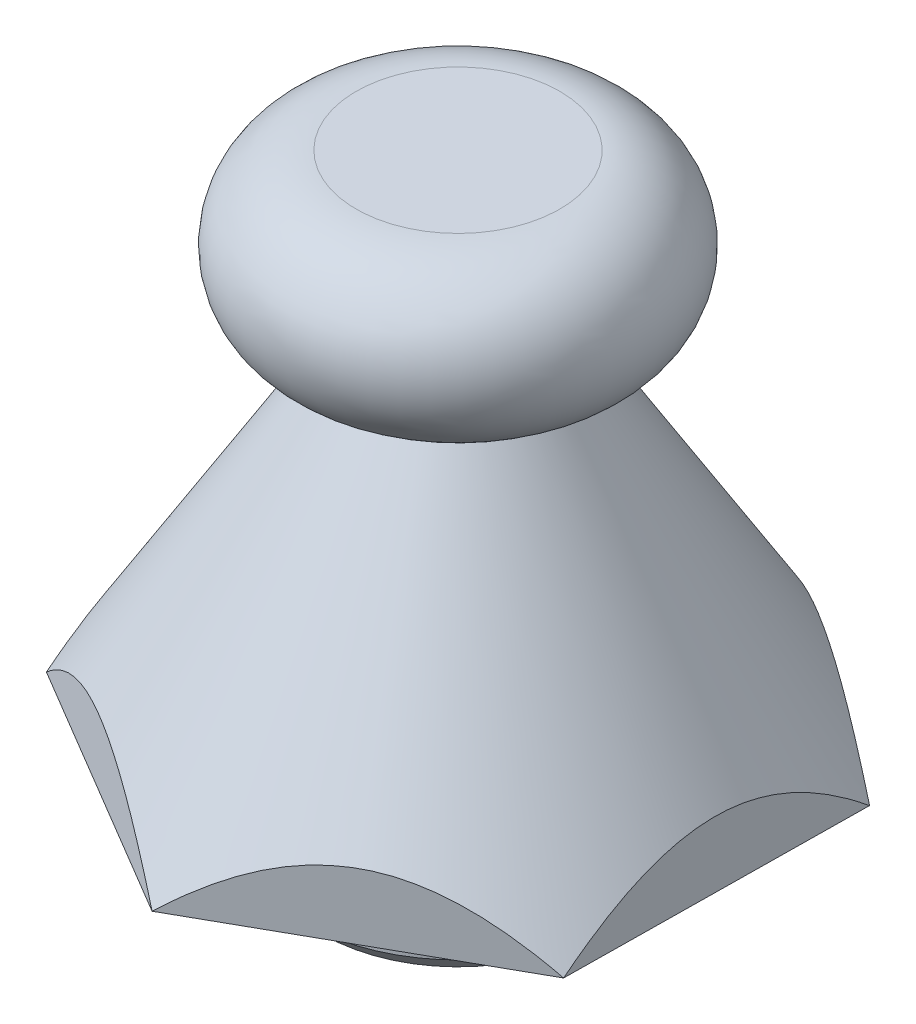
SolidWorks part; units mm, degrees
ref_plane "Front Plane" through (0, 0, 0) normal (0, 0, 1) x (1, 0, 0)
ref_plane "Top Plane" through (0, 0, 0) normal (0, 1, 0) x (1, 0, 0)
ref_plane "Right Plane" through (0, 0, 0) normal (1, 0, 0) x (0, 0, -1)
sketch "Sketch1" plane through (0, 0, 0) normal (0, 0, 1) x (1, 0, 0)
  line L0 (0, 0) -> (0, 30) construction
  line L1 (0, 30) -> (-5, 30)
  line L2 (-4.3701, 22.0499) -> (-14.8248, 5)
  line L3 (-14.8248, 5) -> (-7.6271, 5)
  line L4 (-7.6271, 5) -> (-7.6271, 0)
  line L5 (-7.6271, 0) -> (0, 0)
  line L6 (0, 0) -> (0, 30)
  arc A0 (-5, 30) -> (-4.3701, 22.0499) centre (-5, 26) ccw
  dimension "D3" = 4
  dimension "D1" = 5
  dimension "D2" = 20
  dimension "D4" = 5
  dimension "D5" = 30
  dimension "D6" = 58.484
  dimension "D7" = 7.1977
revolve "Revolve1" add sketch "Sketch1" angle 360 about L0
sketch "Sketch2" plane through (0, 30, 0) normal (0, 1, 0) x (1, 0, 0)
  line L1 (-12.9275, -7.2565) -> (-0.1795, -14.8237)
  line L2 (-0.1795, -14.8237) -> (12.748, -7.5673)
  line L3 (12.748, -7.5673) -> (12.9275, 7.2565)
  line L4 (12.9275, 7.2565) -> (0.1795, 14.8237)
  line L5 (0.1795, 14.8237) -> (-12.748, 7.5673)
  line L6 (-12.748, 7.5673) -> (-12.9275, -7.2565)
  circle A0 centre (0, 0) radius 12.8387 construction
extrude "Cut-Extrude1" cut sketch "Sketch2" against normal through all flip side to cut
chamfer "Chamfer1" distance 1 angle 45 1 edges at (0, 0, -7.6271)
